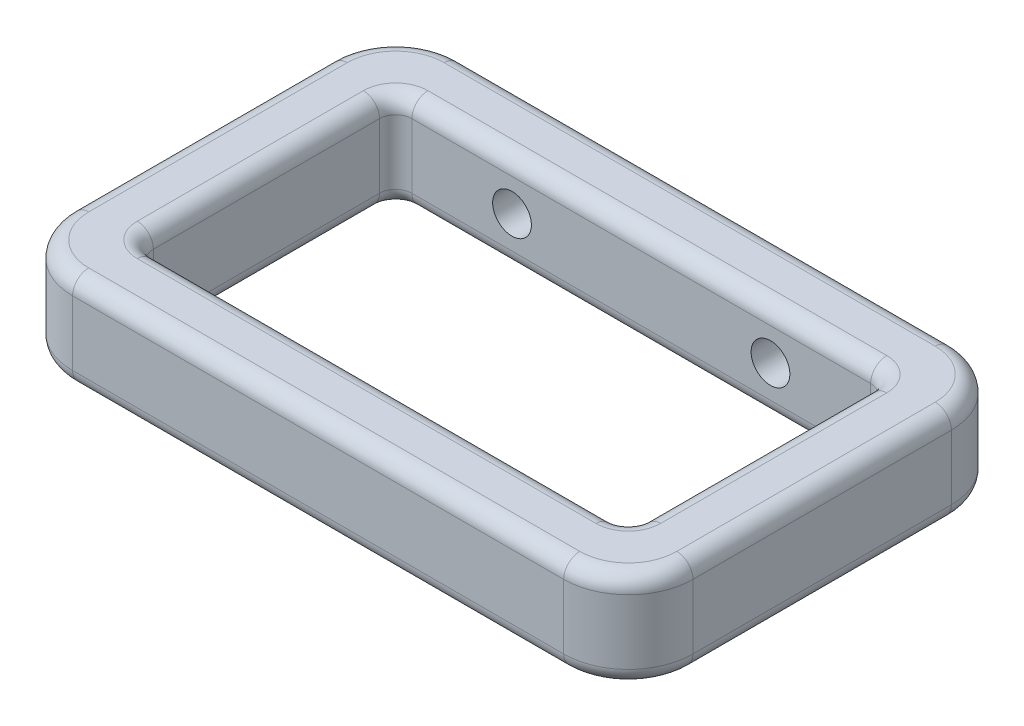
SolidWorks part; units mm, degrees
ref_plane "Front Plane" through (0, 0, 0) normal (0, 0, 1) x (1, 0, 0)
ref_plane "Top Plane" through (0, 0, 0) normal (0, 1, 0) x (1, 0, 0)
ref_plane "Right Plane" through (0, 0, 0) normal (1, 0, 0) x (0, 0, -1)
sketch "Sketch1" plane through (0, 0, 0) normal (0, 1, 0) x (1, 0, 0)
  line L0 (-54.61, 6.35) -> (6.35, 6.35)
  line L1 (0, 0) -> (-48.26, 0)
  line L2 (0, 0) -> (0, -25.4)
  line L3 (0, -25.4) -> (-48.26, -25.4)
  line L4 (-48.26, 0) -> (-48.26, -25.4)
  line L5 (6.35, 6.35) -> (6.35, -31.75)
  line L6 (6.35, -31.75) -> (-54.61, -31.75)
  line L7 (-54.61, -31.75) -> (-54.61, 6.35)
  point P7 (3.6969, -27.7174)
  point P10 (-52.8807, 6.8411)
  dimension "D1" = 48.26
  dimension "D2" = 25.4
  dimension "D3" = 6.35
  dimension "D4" = 6.35
  dimension "D5" = 6.35
  dimension "D6" = 6.35
extrude "Boss-Extrude1" add sketch "Sketch1" along normal blind 9.525
sketch "Sketch2" plane through (0, 0, 0) normal (0, 0, 1) x (1, 0, 0)
  line L0 (-36.83, 4.7625) -> (-54.61, 4.7625) construction
  line L1 (-54.61, 9.525) -> (-54.61, 0) construction
  line L2 (-11.43, 4.7625) -> (6.35, 4.7625) construction
  line L3 (6.35, 9.525) -> (6.35, 0) construction
  line L4 (-54.61, 9.525) -> (6.35, 9.525) construction
  circle A0 centre (-36.83, 4.7625) radius 1.905
  circle A1 centre (-11.43, 4.7625) radius 1.905
  point P12 (0, 0)
  dimension "D3" = 3.81
  dimension "D1" = 25.4
  dimension "D2" = 4.7625
extrude "Cut-Extrude1" cut sketch "Sketch2" against normal through all
fillet "Fillet1" radius 6.35 4 edges at (-54.61, 4.7625, 31.75) (-54.61, 4.7625, -6.35) (6.35, 4.7625, -6.35) (6.35, 4.7625, 31.75)
fillet "Fillet2" radius 1.5875 28 edges at (-48.26, 0, 12.7) (-24.13, 0, 0) (0, 0, 12.7) (-24.13, 0, 25.4) (4.4901, 0, 29.8901) (6.35, 0, 12.7) (4.4901, 0, -4.4901) (-24.13, 0, -6.35) (-52.7501, 0, -4.4901) (-54.61, 0, 12.7) (-52.7501, 0, 29.8901) (-24.13, 0, 31.75) (-24.13, 9.525, 0) (-48.26, 9.525, 12.7) (-24.13, 9.525, 25.4) (0, 9.525, 12.7) (-52.7501, 9.525, -4.4901) (-24.13, 9.525, -6.35) (4.4901, 9.525, -4.4901) (6.35, 9.525, 12.7) (4.4901, 9.525, 29.8901) (-24.13, 9.525, 31.75) (-52.7501, 9.525, 29.8901) (-54.61, 9.525, 12.7) (-48.26, 4.7625, 25.4) (0, 4.7625, 25.4) (0, 4.7625, 0) (-48.26, 4.7625, 0)
